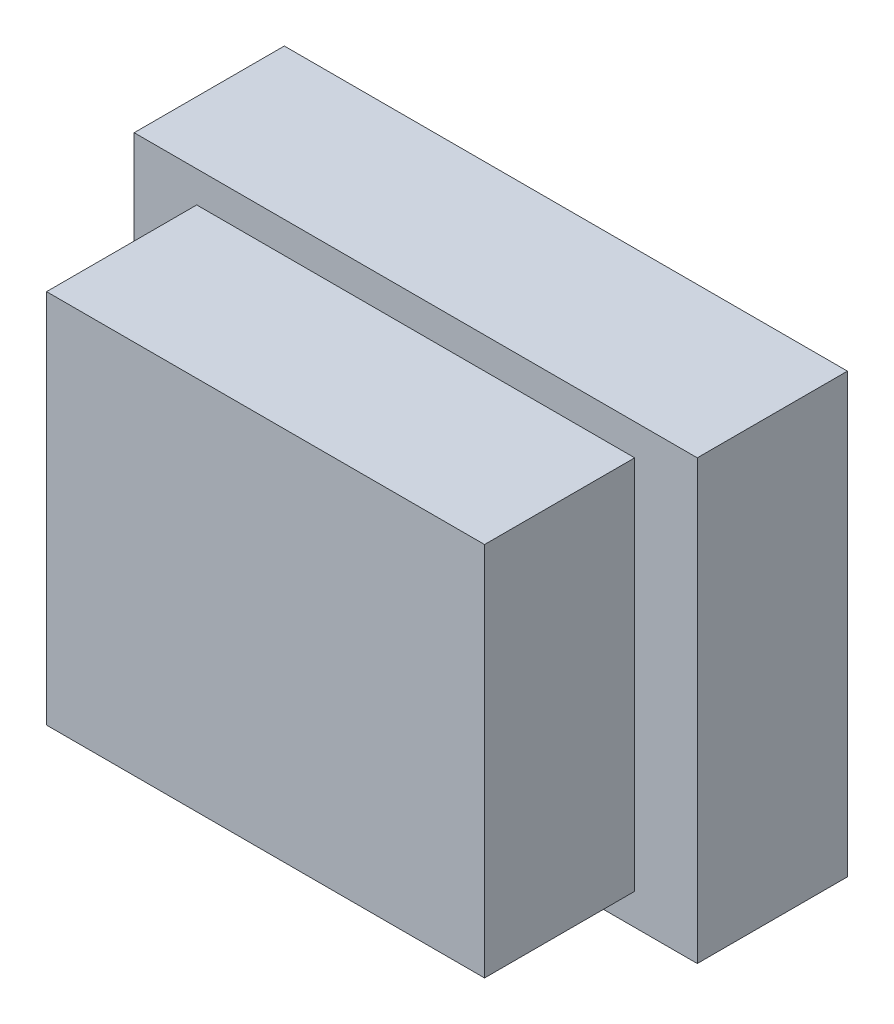
SolidWorks part; units mm, degrees
ref_plane "前视基准面" through (0, 0, 0) normal (0, 0, 1) x (1, 0, 0)
ref_plane "上视基准面" through (0, 0, 0) normal (0, 1, 0) x (1, 0, 0)
ref_plane "右视基准面" through (0, 0, 0) normal (1, 0, 0) x (0, 0, -1)
other "Configuration Table"
sketch "草图1" plane through (0, 0, 0) normal (0, 0, 1) x (1, 0, 0)
  line L0 (-45, -35) -> (45, -35)
  line L1 (45, -35) -> (45, 35)
  line L2 (45, 35) -> (-45, 35)
  line L3 (-45, 35) -> (-45, -35)
extrude "凸台-拉伸1" add sketch "草图1" along normal blind 48
sketch "草图2" plane through (0, 0, 48) normal (0, 0, 1) x (1, 0, 0)
  line L0 (-35, -30) -> (35, -30)
  line L1 (35, -30) -> (35, 30)
  line L2 (35, 30) -> (-35, 30)
  line L3 (-35, 30) -> (-35, -30)
extrude "切除-拉伸1" cut sketch "草图2" against normal blind 24 flip side to cut
